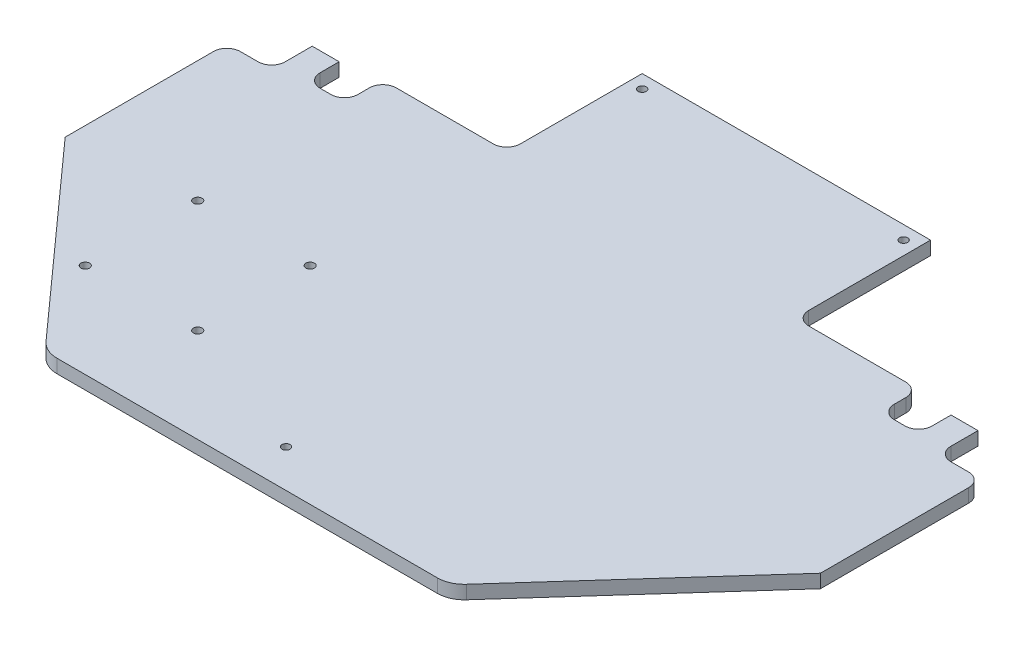
SolidWorks part; units mm, degrees
material "ABS PC"
ref_plane "Plan de face" through (0, 0, 0) normal (0, 0, 1) x (1, 0, 0)
ref_plane "Plan de dessus" through (0, 0, 0) normal (0, 1, 0) x (1, 0, 0)
ref_plane "Plan de droite" through (0, 0, 0) normal (1, 0, 0) x (0, 0, -1)
sketch "Esquisse1" plane through (0, 0, 0) normal (0, 1, 0) x (1, 0, 0)
  line L0 (-101.1, -245.0829) -> (-95, -245.0829) construction
  line L1 (-140.1, 31.2) -> (140.1, 31.2)
  line L2 (-140.1, 31.2) -> (-140.1, -245.0829)
  line L3 (-140.1, -245.0829) -> (140.1, -245.0829)
  line L4 (140.1, 31.2) -> (140.1, -245.0829)
  line L8 (-114.5, 31.2) -> (114.5, 31.2) construction
  line L9 (-140.1, 4) -> (-140.1, -4) construction
  line L10 (140.1, -4) -> (140.1, 4) construction
extrude "Boss.-Extru.1" add sketch "Esquisse1" along normal blind 5
sketch "Esquisse4" plane through (0, 5, 0) normal (0, 1, 0) x (1, 0, 0)
  line L0 (140.1, -245.0829) -> (101.1, -245.0829)
  line L1 (140.1, -245.0829) -> (140.1, -206.0829)
  line L2 (-101.1, -245.0829) -> (-140.1, -245.0829)
  line L3 (-140.1, -245.0829) -> (-140.1, -206.0829)
  arc A1 (101.1, -245.0829) -> (140.1, -206.0829) centre (101.1, -206.0829) ccw
  arc A3 (-140.1, -206.0829) -> (-101.1, -245.0829) centre (-101.1, -206.0829) ccw
  arc A4 (101.1, -245.0829) -> (140.1, -206.0829) centre (101.1, -206.0829) ccw construction
  arc A5 (-140.1, -206.0829) -> (-101.1, -245.0829) centre (-101.1, -206.0829) ccw construction
extrude "Enlèv. mat.-Extru.3" cut sketch "Esquisse4" against normal through all
sketch "Esquisse6" plane through (0, 5, 0) normal (0, 1, 0) x (1, 0, 0)
  line L0 (99.5, 0) -> (99.5, 26.9) construction
  line L1 (140.1, 31.2) -> (53.5, 31.2)
  line L2 (140.1, 31.2) -> (140.1, -41.25)
  line L3 (135.1, -36.25) -> (128.5, -36.25)
  line L4 (99.5, -24) -> (99.5, -28.25)
  line L5 (94.5, -19) -> (58.5, -19)
  line L6 (53.5, -14) -> (53.5, 31.2)
  line L9 (55.5, 15) -> (55.5, -15) construction
  line L10 (88, -16) -> (89, -16) construction
  line L11 (-53.5, -14) -> (-53.5, 31.2)
  line L12 (-94.5, -19) -> (-58.5, -19)
  line L13 (-99.5, -24) -> (-99.5, -28.25)
  line L14 (129.94, -36.25) -> (140.1, -36.25) construction
  line L15 (-135.1, -36.25) -> (-128.5, -36.25)
  line L16 (-140.1, 31.2) -> (-140.1, -41.25)
  line L17 (-140.1, 31.2) -> (-53.5, 31.2)
  line L18 (113.5, -28.25) -> (113.5, -21.2)
  line L19 (113.5, -21.2) -> (123.5, -21.2)
  line L20 (123.5, -21.2) -> (123.5, -31.25)
  line L21 (108.5, -33.25) -> (104.5, -33.25)
  line L22 (-123.5, -21.2) -> (-123.5, -31.25)
  line L23 (-113.5, -21.2) -> (-123.5, -21.2)
  line L24 (-113.5, -28.25) -> (-113.5, -21.2)
  line L25 (0, 0) -> (0, 86.4947) construction
  line L26 (-108.5, -33.25) -> (-104.5, -33.25)
  line L27 (140.1, 36.25) -> (140.1, -245.0829) construction
  arc A0 (140.1, -41.25) -> (135.1, -36.25) centre (135.1, -41.25) ccw
  arc A1 (-99.5, -24) -> (-94.5, -19) centre (-94.5, -24) cw
  arc A2 (58.5, -19) -> (53.5, -14) centre (58.5, -14) cw
  arc A3 (-104.5, -33.25) -> (-99.5, -28.25) centre (-104.5, -28.25) ccw
  arc A4 (104.5, -33.25) -> (99.5, -28.25) centre (104.5, -28.25) cw
  arc A5 (99.5, -24) -> (94.5, -19) centre (94.5, -24) ccw
  arc A6 (-58.5, -19) -> (-53.5, -14) centre (-58.5, -14) ccw
  arc A7 (-140.1, -41.25) -> (-135.1, -36.25) centre (-135.1, -41.25) cw
  arc A8 (113.5, -28.25) -> (108.5, -33.25) centre (108.5, -28.25) cw
  arc A9 (123.5, -31.25) -> (128.5, -36.25) centre (128.5, -31.25) ccw
  arc A10 (-123.5, -31.25) -> (-128.5, -36.25) centre (-128.5, -31.25) cw
  arc A11 (-113.5, -28.25) -> (-108.5, -33.25) centre (-108.5, -28.25) ccw
  point P41 (99.5, -36.25)
  point P43 (99.5, -19)
  point P49 (0, 21.2)
  point P58 (113.5, -33.25)
  dimension "D1" = 5
  dimension "D4" = 3
  dimension "D2" = 2
  dimension "D3" = 3
extrude "Enlèv. mat.-Extru.5" cut sketch "Esquisse6" against normal through all
sketch "Esquisse8" plane through (0, 0, 0) normal (0, -1, 0) x (1, 0, 0)
  line L2 (0, 0) -> (0, -63.4963) construction
  line L4 (53.5, -31.2) -> (53.5, 14) construction
  line L5 (53.5, -31.2) -> (-53.5, -31.2) construction
  line L6 (-53.5, 14) -> (-53.5, -31.2) construction
  circle A0 centre (-48.5, -26.2) radius 1.5
  circle A1 centre (48.5, -26.2) radius 1.5
  dimension "D1" = 3
  dimension "D4" = 5
  dimension "D2" = 3
  dimension "D3" = 5
  dimension "D5" = 5
  dimension "D6" = 5
extrude "Enlèv. mat.-Extru.8" cut sketch "Esquisse8" against normal through all
sketch "Esquisse12" plane through (0, 5, 0) normal (0, 1, 0) x (1, 0, 0)
  line L0 (-140.1, -96.25) -> (-75, -168.8)
  line L3 (-75, -168.8) -> (75, -168.8)
  line L4 (75, -168.8) -> (140.1, -96.25)
  line L5 (140.1, -206.0829) -> (140.1, -41.25) construction
  line L6 (-140.1, -41.25) -> (-140.1, -206.0829) construction
  line L9 (-140.1, -96.25) -> (-140.1, -294.9836)
  line L10 (-140.1, -294.9836) -> (146.0328, -294.9836)
  line L11 (146.0328, -294.9836) -> (140.1, -96.25)
  line L12 (128.5, -36.25) -> (135.1, -36.25) construction
  line L13 (-135.1, -36.25) -> (-128.5, -36.25) construction
  line L14 (53.5, 31.2) -> (-53.5, 31.2) construction
  dimension "D1" = 60
  dimension "D2" = 60
  dimension "D3" = 200
  dimension "D4" = 150
  dimension "D5" = 65.1
extrude "Enlèv. mat.-Extru.15" cut sketch "Esquisse12" against normal through all
fillet "Congé1" radius 10 2 edges at (-75, 2.5, 168.8) (75, 2.5, 168.8)
sketch "Esquisse13" plane through (0, 5, 0) normal (0, 1, 0) x (1, 0, 0)
  line L0 (70.5375, -168.8) -> (-70.5375, -168.8) construction
  circle A0 centre (0.3874, -154.8) radius 1.5
  arc A1 (-77.9803, -165.4786) -> (-70.5375, -168.8) centre (-70.5375, -158.8) ccw construction
  point P9 (-74.6126, -167.932)
  dimension "D2" = 75
  dimension "D3" = 3
  dimension "D1" = 14
extrude "Enlèv. mat.-Extru.16" cut sketch "Esquisse13" against normal through all
sketch "Esquisse14" plane through (0, 5, 0) normal (0, 1, 0) x (1, 0, 0)
  line L0 (70.5375, -168.8) -> (-70.5375, -168.8) construction
  line L2 (-140.1, -41.25) -> (-140.1, -96.25) construction
  circle A0 centre (-95.1, -133.8) radius 1.6
  circle A1 centre (-53.38, -133.8) radius 1.6
  circle A2 centre (-95.1, -92.08) radius 1.6
  circle A3 centre (-53.38, -92.08) radius 1.6
  dimension "D5" = 3.2
  dimension "D6" = 3.2
  dimension "D7" = 3.2
  dimension "D8" = 3.2
  dimension "D9" = 35
  dimension "D11" = 45
  dimension "D10" = 45
  dimension "D1" = 41.72
  dimension "D2" = 41.72
  dimension "D3" = 41.72
  dimension "D4" = 41.72
  dimension "D12" = 35
extrude "Enlèv. mat.-Extru.17" cut sketch "Esquisse14" against normal through all
